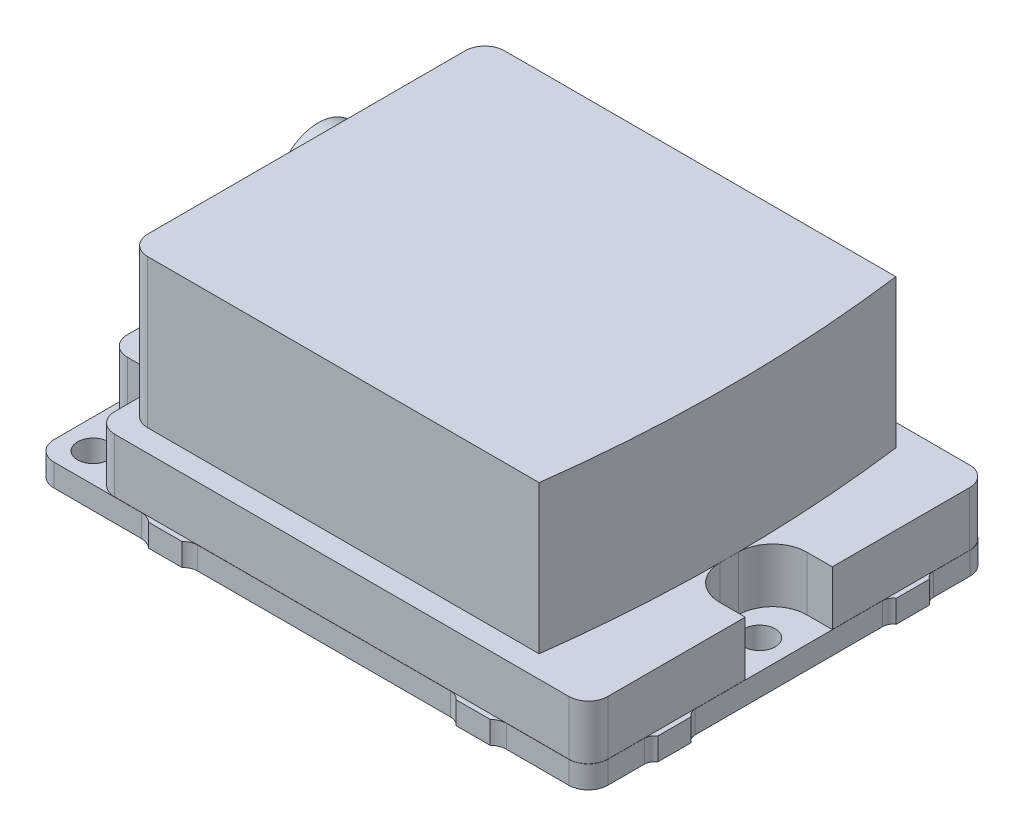
SolidWorks part; units mm, degrees
ref_plane "Front Plane" through (0, 0, 0) normal (0, 0, 1) x (1, 0, 0)
ref_plane "Top Plane" through (0, 0, 0) normal (0, 1, 0) x (1, 0, 0)
ref_plane "Right Plane" through (0, 0, 0) normal (1, 0, 0) x (0, 0, -1)
sketch "Sketch1" plane through (0, 0, 0) normal (0, 1, 0) x (1, 0, 0)
  line L1 (-28.3, -20.5) -> (28.3, -20.5)
  line L2 (-28.3, -20.5) -> (-28.3, 20.5)
  line L3 (-28.3, 20.5) -> (28.3, 20.5)
  line L4 (28.3, -20.5) -> (28.3, 20.5)
  line L5 (-28.3, -20.5) -> (28.3, 20.5) construction
  line L6 (-28.3, 20.5) -> (28.3, -20.5) construction
  point P0 (0, 0)
extrude "Boss-Extrude1" add sketch "Sketch1" along normal blind 2.3
sketch "Sketch2" plane through (0, 2.3, 0) normal (0, 1, 0) x (1, 0, 0)
  line L0 (0, 0) -> (0, 12.239) construction
  line L1 (28.285, -20.48) -> (-28.285, -20.48)
  line L2 (28.285, -20.48) -> (28.285, 20.48)
  line L3 (28.285, 20.48) -> (-28.285, 20.48)
  line L4 (-28.285, -20.48) -> (-28.285, 20.48)
  line L5 (28.285, -20.48) -> (-28.285, 20.48) construction
  line L6 (28.285, 20.48) -> (-28.285, -20.48) construction
  line L7 (0, 0) -> (13.1918, 0) construction
  line L8 (22.185, 0) -> (28.285, 0) construction
  line L9 (-28.285, 13.02) -> (-22.125, 13.02)
  line L10 (-22.125, 13.02) -> (-22.125, 20.48)
  line L11 (28.285, 4.45) -> (22.185, 4.45)
  line L12 (28.285, 4.45) -> (28.285, -4.45)
  line L13 (28.285, -4.45) -> (22.185, -4.45)
  line L14 (-28.285, -13.02) -> (-22.125, -13.02)
  line L15 (-22.125, -13.02) -> (-22.125, -20.48)
  line L16 (22.185, 4.45) -> (22.185, -4.45)
  line L17 (-28.285, 13.02) -> (-28.285, 20.48)
  line L18 (-28.285, -13.02) -> (-28.285, -20.48)
  point P0 (0, 0)
extrude "Boss-Extrude2" add sketch "Sketch2" along normal blind 5.55 contours L16 L11 L2 L3 L10 L9 L4 L14 L15 L1 L13
sketch "Sketch3" plane through (0, 7.85, 0) normal (0, 1, 0) x (1, 0, 0)
  line L1 (-19, -18.225) -> (21, -18.225)
  line L2 (-21, -16.225) -> (-21, 16.225)
  line L3 (-19, 18.225) -> (21, 18.225)
  line L5 (-21, -18.225) -> (21, 18.225) construction
  line L6 (-21, 18.225) -> (21, -18.225) construction
  arc A0 (21, -18.225) -> (21, 18.225) centre (-118.5554, 0) ccw
  arc A1 (-21, 16.225) -> (-19, 18.225) centre (-19, 16.225) cw
  arc A2 (-21, -16.225) -> (-19, -18.225) centre (-19, -16.225) ccw
  point P0 (0, 0)
  dimension "D1" = 2
extrude "Boss-Extrude3" add sketch "Sketch3" along normal blind 15.15
fillet "Fillet1" radius 2 12 edges at (-22.125, 5.075, -13.02) (-28.285, 5.075, -13.02) (-22.125, 5.075, -20.48) (-28.285, 5.075, 13.02) (-22.125, 5.075, 13.02) (-22.125, 5.075, 20.48) (28.3, 1.15, 20.5) (28.285, 5.075, 20.48) (28.3, 1.15, -20.5) (28.285, 5.075, -20.48) (-28.3, 1.15, 20.5) (-28.3, 1.15, -20.5)
sketch "Sketch4" plane through (0, 0, 0) normal (0, 1, 0) x (1, 0, 0)
  line L0 (28.785, 12.18) -> (29.8277, 12.18) construction
  line L1 (28.285, 4.45) -> (28.285, 18.48) construction
  line L4 (28.285, 13.88) -> (28.285, 10.48)
  line L6 (28.785, 13.88) -> (28.785, 10.48)
  line L7 (28.3, -18.5) -> (28.3, 18.5) construction
  line L8 (28.3, 14.7724) -> (28.3, 9.5876)
  line L9 (28.3, 0) -> (32.8587, 0) construction
  line L10 (28.785, -13.88) -> (28.785, -10.48)
  line L11 (28.3, -14.7724) -> (28.3, -9.5876)
  arc A0 (28.3, 14.7724) -> (28.785, 13.88) centre (29.3634, 14.7724) ccw
  arc A1 (28.3, 9.5876) -> (28.785, 10.48) centre (29.3634, 9.5876) cw
  arc A2 (28.3, -14.7724) -> (28.785, -13.88) centre (29.3634, -14.7724) cw
  arc A3 (28.3, -9.5876) -> (28.785, -10.48) centre (29.3634, -9.5876) ccw
  dimension "D2" = 3.4
extrude "Boss-Extrude5" add sketch "Sketch4" along direction (0, -1, 0) on the side of the normal up to surface (2.3 mm away) contours L8 A1 L6 A0 | A3 L11 A2 L10
sketch "Sketch5" plane through (29.4347, 0, -17.005) normal (0, 1, 0) x (0, 0, -1)
  line L2 (-37.505, 43.871) -> (-37.99, 43.871) construction
  line L3 (3.495, 3.1347) -> (3.495, 55.7347) construction
  line L4 (3.495, 9.6293) -> (3.495, 9.4863)
  line L5 (-37.505, 12.4285) -> (-37.99, 12.4285) construction
  line L6 (3.98, 14.1497) -> (3.98, 10.7072)
  line L8 (3.495, 15.2277) -> (3.495, 9.6293)
  line L9 (-12.555, 1.1497) -> (1.475, 1.1497) construction
  line L10 (3.495, 12.4285) -> (3.98, 12.4285) construction
  line L11 (-37.505, 46.8132) -> (-37.505, 46.6702)
  line L12 (3.495, 43.871) -> (3.98, 43.871) construction
  line L13 (3.495, 41.0718) -> (3.495, 46.6702)
  line L14 (3.98, 42.1497) -> (3.98, 45.5922)
  line L15 (-17.005, 57.7197) -> (-17.005, 64.4158) construction
  line L16 (-28.025, 57.7197) -> (-5.985, 57.7197) construction
  line L17 (3.495, 46.8132) -> (3.495, 46.6702)
  line L18 (-37.99, 42.1497) -> (-37.99, 45.5922)
  line L19 (-37.505, 41.0718) -> (-37.505, 46.6702)
  line L20 (-37.505, 15.2277) -> (-37.505, 9.6293)
  line L21 (-37.99, 14.1497) -> (-37.99, 10.7072)
  line L22 (-37.505, 9.6293) -> (-37.505, 9.4863)
  arc A2 (3.495, 15.2277) -> (3.98, 14.1497) centre (4.9354, 15.2277) ccw
  arc A3 (3.98, 10.7072) -> (3.495, 9.4863) centre (5.2744, 9.4863) ccw
  arc A4 (3.98, 45.5922) -> (3.495, 46.8132) centre (5.2744, 46.8132) cw
  arc A5 (3.495, 41.0718) -> (3.98, 42.1497) centre (4.9354, 41.0718) cw
  arc A6 (-37.505, 41.0718) -> (-37.99, 42.1497) centre (-38.9454, 41.0718) ccw
  arc A7 (-37.99, 45.5922) -> (-37.505, 46.8132) centre (-39.2844, 46.8132) ccw
  arc A8 (-37.99, 10.7072) -> (-37.505, 9.4863) centre (-39.2844, 9.4863) cw
  arc A9 (-37.505, 15.2277) -> (-37.99, 14.1497) centre (-38.9454, 15.2277) cw
  dimension "D4" = 0.485
  dimension "D2" = 13
  dimension "D5" = 0.485
extrude "Boss-Extrude6" add sketch "Sketch5" along normal up to surface (2.3 mm away) up to face at (-3.803, 2.3, 0)
sketch "Sketch6" plane through (0, 2.3, 0) normal (0, 1, 0) x (1, 0, 0)
  line L0 (-17.3785, 20.5) -> (-26.3, 20.5) construction
  line L1 (-28.3, 18.5) -> (-28.3, -18.5) construction
  line L2 (-28.3, 0) -> (-40.154, 0) construction
  line L3 (28.3, -9.5876) -> (28.3, 9.5876) construction
  line L4 (-21, 0) -> (36.0528, 0) construction
  line L5 (-21, 16.225) -> (-21, -16.225) construction
  circle A0 centre (-25.3, 17.5) radius 1.6
  circle A1 centre (-25.3, -17.5) radius 1.6
  circle A2 centre (25.3, 0) radius 1.6
  point P15 (0, 0)
  dimension "D1" = 3
  dimension "D3" = 3
  dimension "D2" = 3
extrude "Cut-Extrude1" cut sketch "Sketch6" against normal through all
fillet "Fillet2" radius 3.5 2 edges at (22.185, 5.075, 4.45) (22.185, 5.075, -4.45)
sketch "Sketch7" plane through (-21, 0, 0) normal (-1, 0, 0) x (0, 0, 1)
  line L0 (18.225, 23) -> (18.225, 7.85) construction
  line L1 (-16.225, 23) -> (16.225, 23) construction
  line L2 (-0.5282, 14.265) -> (-0.5282, 17.2665) construction
  line L3 (2.3518, 14.265) -> (2.3518, 17.2665) construction
  line L4 (-6.66, 20.3968) -> (7.06, 20.3968) construction
  circle A0 centre (7.06, 14.265) radius 4.7082
  circle A1 centre (-6.66, 14.265) radius 6.1318 construction
  dimension "D1" = 11.165
  dimension "D2" = 8.735
  dimension "D3" = 2.88
  dimension "D4" = 9.4163
extrude "Boss-Extrude7" add sketch "Sketch7" along normal blind 0.2 contours A0
ref_plane "Plane1" through (0, 0, -6.66) normal (0, 0, -1) x (-1, 0, 0)
sketch "Sketch9" plane through (0, 0, -6.66) normal (0, 0, -1) x (-1, 0, 0)
  line L0 (21, 14.265) -> (24, 14.265) construction
  line L1 (21, 9.5568) -> (21, 18.9732) construction
  line L2 (21, 20.3968) -> (22.15, 20.3968) construction
  line L3 (21, 8.1332) -> (21, 20.3968) construction
  line L4 (21, 23) -> (21, 7.85) construction
  line L5 (21.6362, 18.665) -> (24.6021, 18.665) construction
  line L6 (24, 14.265) -> (24, 18.665) construction
  line L7 (24, 18.665) -> (22.15, 20.3968) construction
  line L8 (21, 20.3968) -> (21, 14.265)
  line L9 (21, 14.265) -> (24, 14.265)
  line L10 (24, 14.265) -> (24, 18.665)
  line L11 (24, 18.665) -> (22.15, 20.3968)
  line L12 (22.15, 20.3968) -> (21, 20.3968)
  dimension "D1" = 4.4
revolve "Revolve1" add sketch "Sketch9" angle 360 about L9
sketch "Sketch11" plane through (-24, 0, 0) normal (-1, 0, 0) x (0, 0, 1)
  circle A0 centre (-6.66, 14.265) radius 4.425
extrude "Boss-Extrude8" add sketch "Sketch11" along normal blind 2.45
sketch "Sketch12" plane through (-26.45, 0, 0) normal (-1, 0, 0) x (0, 0, 1)
  circle A0 centre (-6.66, 14.265) radius 3.925
  circle A1 centre (-6.66, 14.265) radius 4.425 construction
  dimension "D1" = 0.5
extrude "Cut-Extrude2" cut sketch "Sketch12" against normal blind 2.45 and the other way blind 10
sketch "Sketch13" plane through (-21.2, 0, 0) normal (-1, 0, 0) x (0, 0, 1)
  line L0 (7.06, 18.9732) -> (7.06, 9.5568) construction
  line L2 (2.3518, 14.265) -> (4.7059, 10.1876)
  line L3 (4.7059, 10.1876) -> (9.4141, 10.1876)
  line L4 (9.4141, 10.1876) -> (11.7682, 14.265)
  line L5 (11.7682, 14.265) -> (9.4141, 18.3424)
  line L6 (9.4141, 18.3424) -> (4.7059, 18.3424)
  line L7 (4.7059, 18.3424) -> (2.3518, 14.265)
  circle A0 centre (7.06, 14.265) radius 4.7082 construction
  circle A1 centre (7.06, 14.265) radius 4.7082 construction
  circle A2 centre (7.06, 14.265) radius 4.0774 construction
extrude "Boss-Extrude10" add sketch "Sketch13" along normal blind 1
